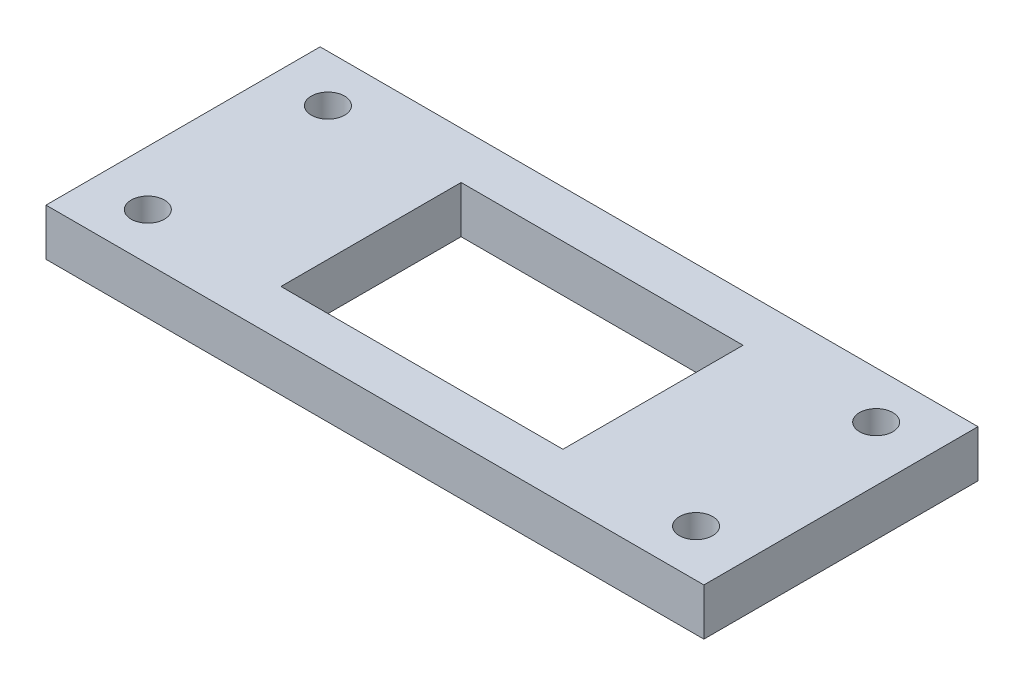
SolidWorks part; units mm, degrees
ref_plane "Front Plane" through (0, 0, 0) normal (0, 0, 1) x (1, 0, 0)
ref_plane "Top Plane" through (0, 0, 0) normal (0, 1, 0) x (1, 0, 0)
ref_plane "Right Plane" through (0, 0, 0) normal (1, 0, 0) x (0, 0, -1)
sketch "Sketch1" plane through (0, 0, 0) normal (0, 1, 0) x (1, 0, 0)
  line L1 (-84, -35) -> (84, -35)
  line L2 (-84, -35) -> (-84, 35)
  line L3 (-84, 35) -> (84, 35)
  line L4 (84, -35) -> (84, 35)
  line L5 (-36, -23) -> (36, -23)
  line L6 (-36, -23) -> (-36, 23)
  line L7 (-36, 23) -> (36, 23)
  line L8 (36, -23) -> (36, 23)
  circle A0 centre (-70, -23) radius 4.25
  circle A1 centre (70, -23) radius 4.25
  circle A2 centre (-70, 23) radius 4.25
  circle A3 centre (70, 23) radius 4.25
extrude "Bridge_Clamp_Extrude" add sketch "Sketch1" along normal blind 12
equation "\"ValveDiameter\" = 50mm"
equation "\"MotorGearTeeth\" = 40"
equation "\"OutputGearTeeth\" = 80"
equation "\"GearModule\" = 1.5mm"
equation "\"PressureAngle\" = 20deg"
equation "\"GearCenterDistance\" = 90mm"
equation "\"GearWidth\" = 18mm"
equation "\"OutputShaftDiameter\" = 20mm"
equation "\"BearingOD\" = 47mm"
equation "\"BearingWidth\" = 14mm"
equation "\"PlateThickness\" = 6mm"
equation "\"ValveRotation\" = 90deg"
